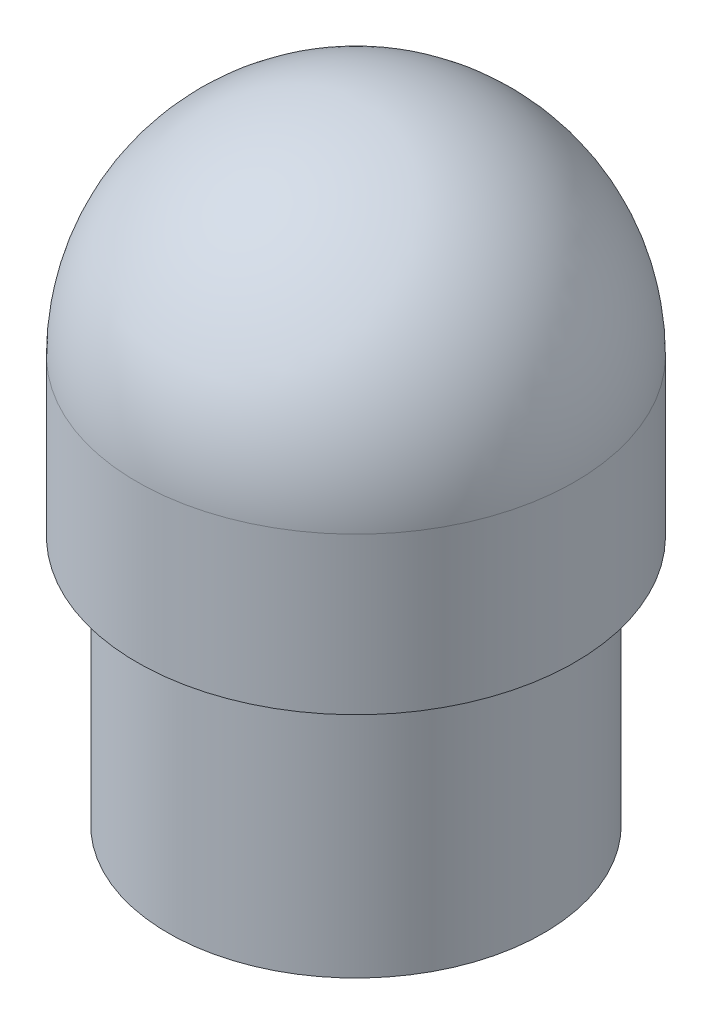
SolidWorks part; units mm, degrees
ref_plane "前基準面" through (0, 0, 0) normal (0, 0, 1) x (1, 0, 0)
ref_plane "上基準面" through (0, 0, 0) normal (0, 1, 0) x (1, 0, 0)
ref_plane "右基準面" through (0, 0, 0) normal (1, 0, 0) x (0, 0, -1)
sketch "草圖1" plane through (0, 0, 0) normal (0, 0, 1) x (1, 0, 0)
  line L1 (0, 0) -> (15, 0)
  line L2 (0, 0) -> (0, 20)
  line L3 (0, 20) -> (15, 20)
  line L4 (15, 0) -> (15, 20)
  line L5 (0, 20) -> (17.5, 20)
  line L6 (0, 20) -> (0, 50)
  line L7 (0, 50) -> (17.5, 50)
  line L8 (17.5, 20) -> (17.5, 50)
  dimension "D1" = 15
  dimension "D2" = 20
  dimension "D3" = 30
  dimension "D4" = 17.5
revolve "旋轉1" add sketch "草圖1" angle 360 about L6
fillet "圓角1" radius 17.5 1 edges at (0, 50, -17.5)
